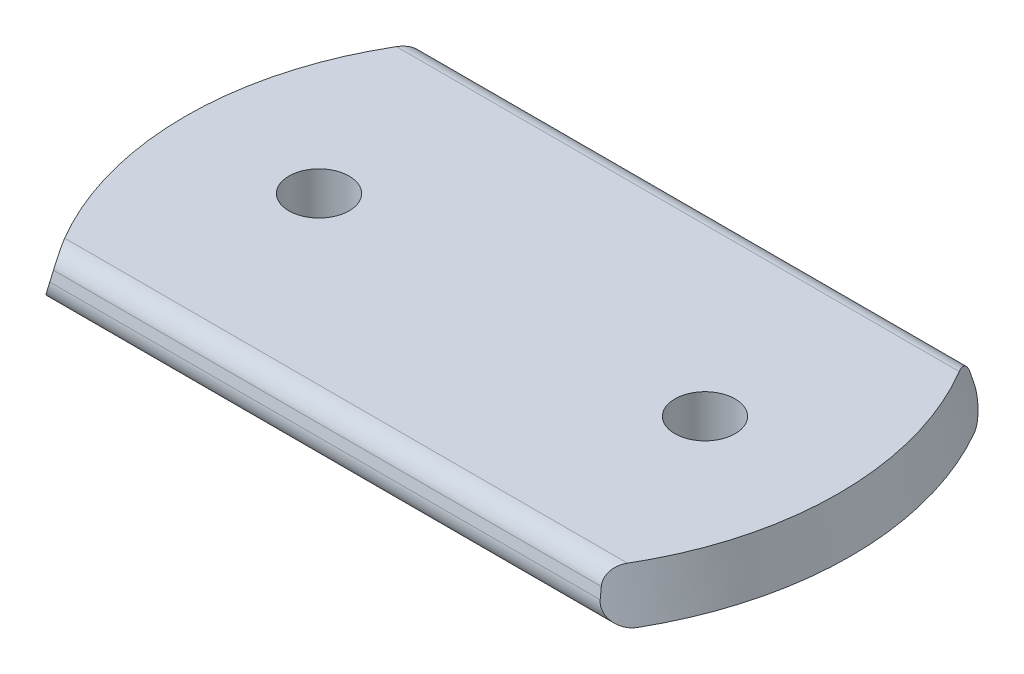
SolidWorks part; units mm, degrees
ref_plane "Front Plane" through (0, 0, 0) normal (0, 0, 1) x (1, 0, 0)
ref_plane "Top Plane" through (0, 0, 0) normal (0, 1, 0) x (1, 0, 0)
ref_plane "Right Plane" through (0, 0, 0) normal (1, 0, 0) x (0, 0, -1)
sketch "Sketch4" plane through (0, 0, 0) normal (0, 1, 0) x (1, 0, 0)
  line L0 (-7.1878, -2.54) -> (7.1878, -2.54)
  line L1 (-7.6234, -2.54) -> (-7.6234, 2.54) construction
  line L2 (7.6234, -2.54) -> (7.6234, 2.54) construction
  line L3 (-7.1878, 2.54) -> (7.1878, 2.54)
  line L4 (-7.6234, -2.54) -> (7.6234, 2.54) construction
  line L5 (7.6234, -2.54) -> (-7.6234, 2.54) construction
  line L6 (-7.6234, 0) -> (7.6234, 0) construction
  line L7 (0, 2.54) -> (0, -2.54) construction
  line L8 (-7.6234, 2.54) -> (7.6234, 2.54) construction
  line L9 (7.6234, -2.54) -> (-7.6234, -2.54) construction
  arc A0 (-7.1878, 2.54) -> (-7.1878, -2.54) centre (0, 0) ccw
  arc A1 (7.1878, 2.54) -> (-7.1878, 2.54) centre (0, 0) ccw construction
  arc A2 (-7.1878, -2.54) -> (7.1878, -2.54) centre (0, 0) ccw construction
  arc A3 (7.1878, -2.54) -> (7.1878, 2.54) centre (0, 0) ccw
  point P5 (0, 0)
  point P10 (2.54, 0)
  point P13 (-2.54, 0)
  dimension "D1" = 15.2468
  dimension "D2" = 5.08
  dimension "D3" = 2.54
sketch "Sketch1" plane through (0, 0, 0) normal (0, 1, 0) x (1, 0, 0)
  line L0 (-3.6633, -2.54) -> (3.6633, -2.54)
  line L1 (-4.4577, -2.54) -> (-4.4577, 2.54) construction
  line L2 (4.4577, -2.54) -> (4.4577, 2.54) construction
  line L3 (-3.6633, 2.54) -> (3.6633, 2.54)
  line L4 (-4.4577, -2.54) -> (4.4577, 2.54) construction
  line L5 (4.4577, -2.54) -> (-4.4577, 2.54) construction
  line L6 (-4.4577, 0) -> (4.4577, 0) construction
  line L7 (0, 2.54) -> (0, -2.54) construction
  line L8 (-4.4577, 2.54) -> (4.4577, 2.54) construction
  line L9 (4.4577, -2.54) -> (-4.4577, -2.54) construction
  arc A0 (-3.6633, 2.54) -> (-3.6633, -2.54) centre (0, 0) ccw
  arc A1 (3.6633, 2.54) -> (-3.6633, 2.54) centre (0, 0) ccw construction
  arc A2 (-3.6633, -2.54) -> (3.6633, -2.54) centre (0, 0) ccw construction
  arc A3 (3.6633, -2.54) -> (3.6633, 2.54) centre (0, 0) ccw
  point P5 (0, 0)
  point P10 (2.54, 0)
  point P13 (-2.54, 0)
  dimension "D1" = 8.9154
  dimension "D2" = 5.08
  dimension "D3" = 2.54
extrude "Boss-Extrude1" add sketch "Sketch1" along normal blind 0.635 draft 14
hole_wizard "1/32 (0.03125) Diameter Hole1" positions "Sketch6" profile "Sketch5" hole size "1/32" standard "ANSI Inch"
sketch "Sketch6" plane through (0, 0, 0) normal (0, -1, 0) x (-1, 0, 0)
  point P0 (2.54, 0)
  point P3 (-2.54, 0)
sketch "Sketch5" plane through (-2.54, 0, 0) normal (1, 0, 0) x (0, 0, -1)
  line L0 (0, 0) -> (0, 12.9385)
  line L1 (0, 12.9385) -> (0.3969, 12.7)
  line L2 (0.3969, 12.7) -> (0.3969, 0)
  line L5 (0.3969, 0) -> (0, 0)
  line L10 (0, 12.9385) -> (-0.3969, 12.7) construction
  line L11 (0, -6.35) -> (0, 107.95) construction
  dimension "Hole Dia." = 0.7937
  dimension "Hole Depth" = 12.7
  dimension "Drill Angle" = 118
fillet "Fillet1" radius 0.254 4 edges at (0, 0, -2.54) (0, 0.635, -2.3817) (0, 0, 2.54) (0, 0.635, 2.3817)
